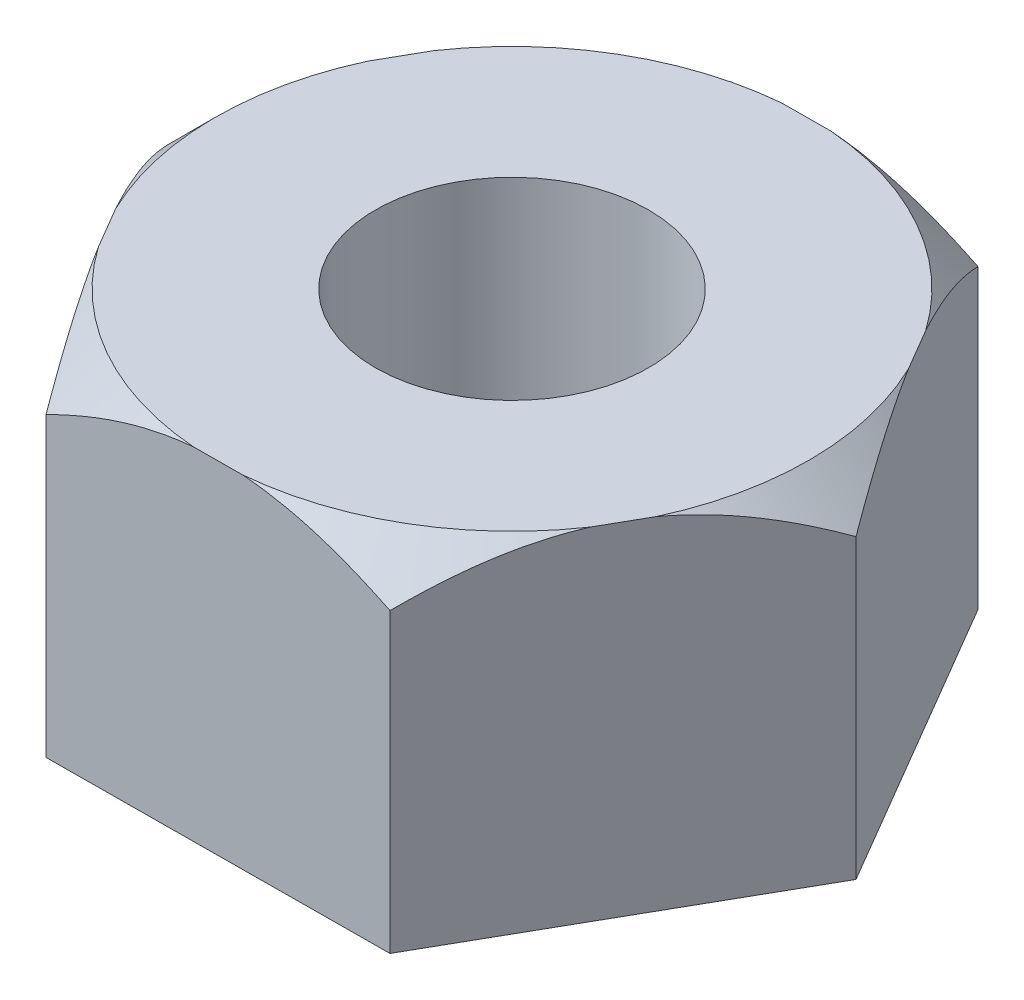
SolidWorks part; units mm, degrees
ref_plane "Front Plane" through (0, 0, 0) normal (0, 0, 1) x (1, 0, 0)
ref_plane "Top Plane" through (0, 0, 0) normal (0, 1, 0) x (1, 0, 0)
ref_plane "Right Plane" through (0, 0, 0) normal (1, 0, 0) x (0, 0, -1)
sketch "Sketch1" plane through (0, 0, 0) normal (0, 1, 0) x (1, 0, 0)
  line L1 (2.5287, -4.3136) -> (5, 0.0331)
  line L2 (5, 0.0331) -> (2.4713, 4.3467)
  line L3 (2.4713, 4.3467) -> (-2.5287, 4.3136)
  line L4 (-2.5287, 4.3136) -> (-5, -0.0331)
  line L5 (-5, -0.0331) -> (-2.4713, -4.3467)
  line L6 (-2.4713, -4.3467) -> (2.5287, -4.3136)
  circle A0 centre (0, 0) radius 4.3302 construction
  circle A1 centre (0, 0) radius 2
  dimension "D2" = 4
  dimension "D1" = 10
extrude "Boss-Extrude1" add sketch "Sketch1" along normal blind 5
sketch "Sketch2" plane through (0, 5, 0) normal (0, 1, 0) x (1, 0, 0)
  circle A0 centre (0, 0) radius 4.3446
extrude "Cut-Extrude1" cut sketch "Sketch2" against normal blind 5 draft 45 flip side to cut
